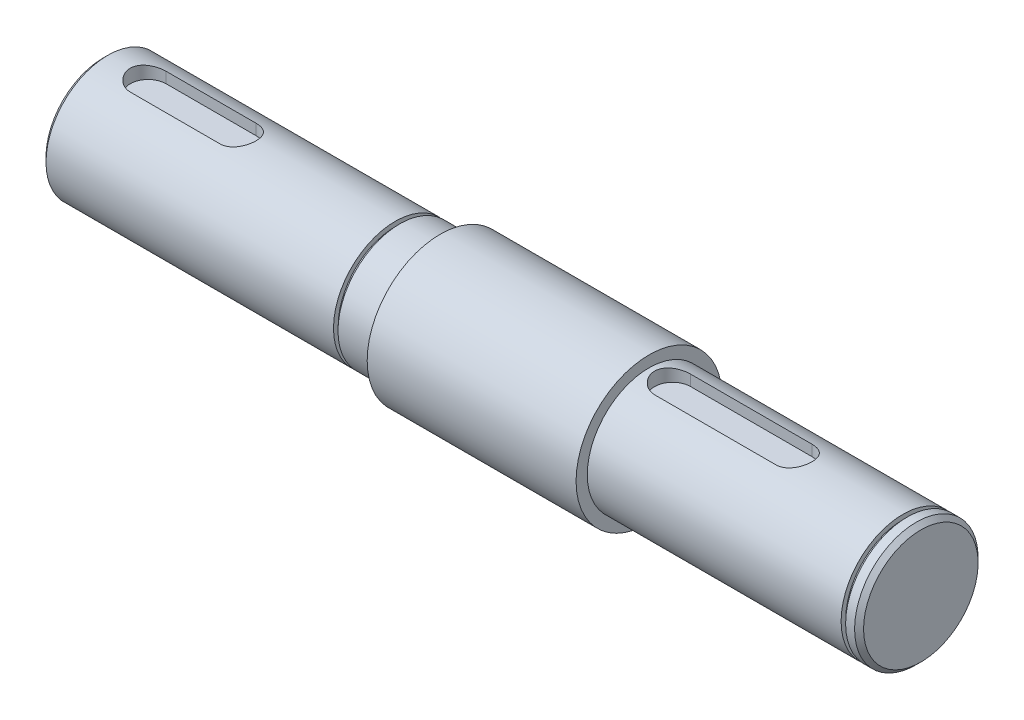
SolidWorks part; units mm, degrees
material "1.0050 (E295)"
ref_plane "Front Plane" through (0, 0, 0) normal (0, 0, 1) x (1, 0, 0)
ref_plane "Top Plane" through (0, 0, 0) normal (0, 1, 0) x (1, 0, 0)
ref_plane "Right Plane" through (0, 0, 0) normal (1, 0, 0) x (0, 0, -1)
sketch "Sketch1" plane through (0, 0, 0) normal (0, 0, 1) x (1, 0, 0)
  line L0 (0, 0) -> (364, 0)
  line L1 (0, 0) -> (0, 25.5)
  line L2 (2, 27.5) -> (130, 27.5)
  line L3 (364, 25.5) -> (364, 0)
  line L4 (362, 27.5) -> (364, 25.5)
  line L5 (356, 27.5) -> (356, 25.4)
  line L6 (356, 25.4) -> (358, 25.4)
  line L7 (358, 25.4) -> (358, 27.5)
  line L8 (358, 27.5) -> (362, 27.5)
  line L9 (150, 27.5) -> (150, 32.5)
  line L10 (150, 32.5) -> (243, 32.5)
  line L11 (243, 32.5) -> (243, 27.5)
  line L12 (132, 27.5) -> (132, 25.4)
  line L13 (132, 25.4) -> (130, 25.4)
  line L14 (130, 25.4) -> (130, 27.5)
  line L15 (0, 25.5) -> (2, 27.5)
  line L16 (132, 27.5) -> (150, 27.5)
  line L17 (243, 27.5) -> (356, 27.5)
  point P4 (0, 27.5)
  point P5 (364, 27.5)
  point P9 (318, 27.5)
  point P14 (348, 27.5)
  dimension "D1" = 27.5
  dimension "D2" = 25.4
  dimension "D3" = 2
  dimension "D5" = 6
  dimension "D6" = 8
  dimension "D7" = 30
  dimension "D8" = 75
  dimension "D9" = 18
  dimension "D10" = 93
  dimension "D11" = 130
  dimension "D12" = 25.4
  dimension "D13" = 2
  dimension "D14" = 5
  dimension "D15" = 2
revolve "Revolve1" add sketch "Sketch1" angle 360 about L0
ref_plane "Plane1" through (0, 27.5, 0) normal (0, 1, 0) x (1, 0, 0)
sketch "Sketch2" plane through (0, 27.5, 0) normal (0, 1, 0) x (1, 0, 0)
  line L0 (0, 0) -> (364, 0) construction
  line L1 (0, 25.5) -> (0, -25.5) construction
  line L2 (364, -25.5) -> (364, 25.5) construction
  line L3 (253.5, 0) -> (307.5, 0) construction
  line L4 (253.5, 8) -> (307.5, 8)
  line L5 (253.5, -8) -> (307.5, -8)
  line L7 (243, -32.5) -> (243, 32.5) construction
  arc A0 (253.5, 8) -> (253.5, -8) centre (253.5, 0) ccw
  arc A1 (307.5, -8) -> (307.5, 8) centre (307.5, 0) ccw
  point P8 (280.5, 0)
  dimension "D1" = 2.5
  dimension "D3" = 70
  dimension "D2" = 16
extrude "Cut-Extrude1" cut sketch "Sketch2" against normal blind 6
ref_plane "Plane2" through (0, 27.5, 0) normal (0, 1, 0) x (1, 0, 0)
sketch "Sketch3" plane through (0, 27.5, 0) normal (0, 1, 0) x (1, 0, 0)
  line L4 (0, 0) -> (132, 0) construction
  line L5 (132, 25.4) -> (132, -25.4) construction
  line L6 (20, 0) -> (60, 0) construction
  line L7 (20, 8) -> (60, 8)
  line L8 (20, -8) -> (60, -8)
  line L9 (0, 25.5) -> (0, -25.5) construction
  arc A4 (20, 8) -> (20, -8) centre (20, 0) ccw
  arc A5 (60, -8) -> (60, 8) centre (60, 0) ccw
  point P13 (40, 0)
  dimension "D4" = 20
  dimension "D2" = 56
  dimension "D3" = 16
extrude "Cut-Extrude2" cut sketch "Sketch3" against normal blind 6
